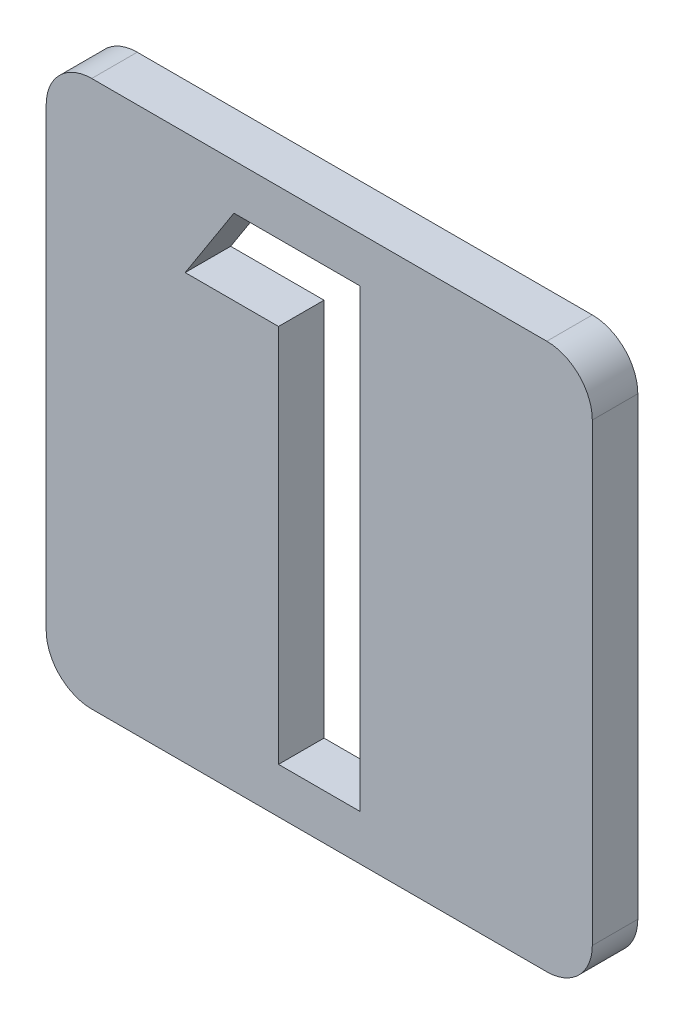
SolidWorks part; units mm, degrees
ref_plane "Front Plane" through (0, 0, 0) normal (0, 0, 1) x (1, 0, 0)
ref_plane "Top Plane" through (0, 0, 0) normal (0, 1, 0) x (1, 0, 0)
ref_plane "Right Plane" through (0, 0, 0) normal (1, 0, 0) x (0, 0, -1)
sketch "Sketch1" plane through (0, 0, 0) normal (0, 0, 1) x (1, 0, 0)
  line L1 (-50, 60) -> (50, 60)
  line L2 (-60, 50) -> (-60, -50)
  line L3 (-50, -60) -> (50, -60)
  line L4 (60, 50) -> (60, -50)
  line L5 (-60, 60) -> (60, -60) construction
  line L6 (-60, -60) -> (60, 60) construction
  arc A0 (-60, -50) -> (-50, -60) centre (-50, -50) ccw
  arc A1 (50, -60) -> (60, -50) centre (50, -50) ccw
  arc A2 (50, 60) -> (60, 50) centre (50, 50) cw
  arc A3 (-50, 60) -> (-60, 50) centre (-50, 50) ccw
  point P0 (0, 0)
  dimension "D3" = 10
  dimension "D1" = 120
  dimension "D2" = 120
extrude "Boss-Extrude1" add sketch "Sketch1" along normal blind 10 contours A3 L2 A0 L3 A1 L4 A2 L1
sketch "Sketch2" plane through (0, 0, 10) normal (0, 0, 1) x (1, 0, 0)
  line L0 (0, 0) -> (0, 40) construction
  line L1 (-50, 50) -> (50, 50) construction
  line L2 (-50, 50) -> (-50, -50) construction
  line L3 (-50, -50) -> (50, -50) construction
  line L4 (50, 50) -> (50, -50) construction
  line L5 (-50, 50) -> (50, -50) construction
  line L6 (-50, -50) -> (50, 50) construction
  line L7 (0, 40) -> (-40, 40) construction
  line L8 (-40, 40) -> (-40, 0) construction
  line L9 (-40, 0) -> (0, 0) construction
  line L11 (0, 20) -> (-20, 20) construction
  line L12 (-20, 40) -> (-20, 20) construction
  circle A0 centre (0, 40) radius 4 construction
  circle A1 centre (0, 20) radius 4 construction
  circle A2 centre (0, 0) radius 4 construction
  circle A3 centre (-20, 20) radius 4 construction
  circle A4 centre (-20, 40) radius 4 construction
  circle A5 centre (-40, 40) radius 4 construction
  circle A6 centre (0, 0) radius 4 construction
  circle A7 centre (20, 0) radius 4 construction
  circle A8 centre (40, 0) radius 4 construction
  circle A9 centre (40, 20) radius 4 construction
  circle A10 centre (40, 40) radius 4 construction
  circle A11 centre (20, 20) radius 4 construction
  circle A12 centre (0, 0) radius 4 construction
  circle A13 centre (0, -20) radius 4 construction
  circle A14 centre (0, -40) radius 4 construction
  circle A15 centre (20, -40) radius 4 construction
  circle A16 centre (40, -40) radius 4 construction
  circle A17 centre (20, -20) radius 4 construction
  circle A18 centre (0, 0) radius 4 construction
  circle A19 centre (-20, 0) radius 4 construction
  circle A20 centre (-40, 0) radius 4 construction
  circle A21 centre (-40, -20) radius 4 construction
  circle A22 centre (-40, -40) radius 4 construction
  circle A23 centre (-20, -20) radius 4 construction
  text T0 "1" font "Century Gothic" height 100
  point P0 (0, 0)
  point P55 (0, 0)
  dimension "D4" = 8
  dimension "D1" = 100
  dimension "D2" = 100
  dimension "D3" = 40
  dimension "D5" = 4
extrude "Cut-Extrude2" cut sketch "Sketch2" against normal blind 10
